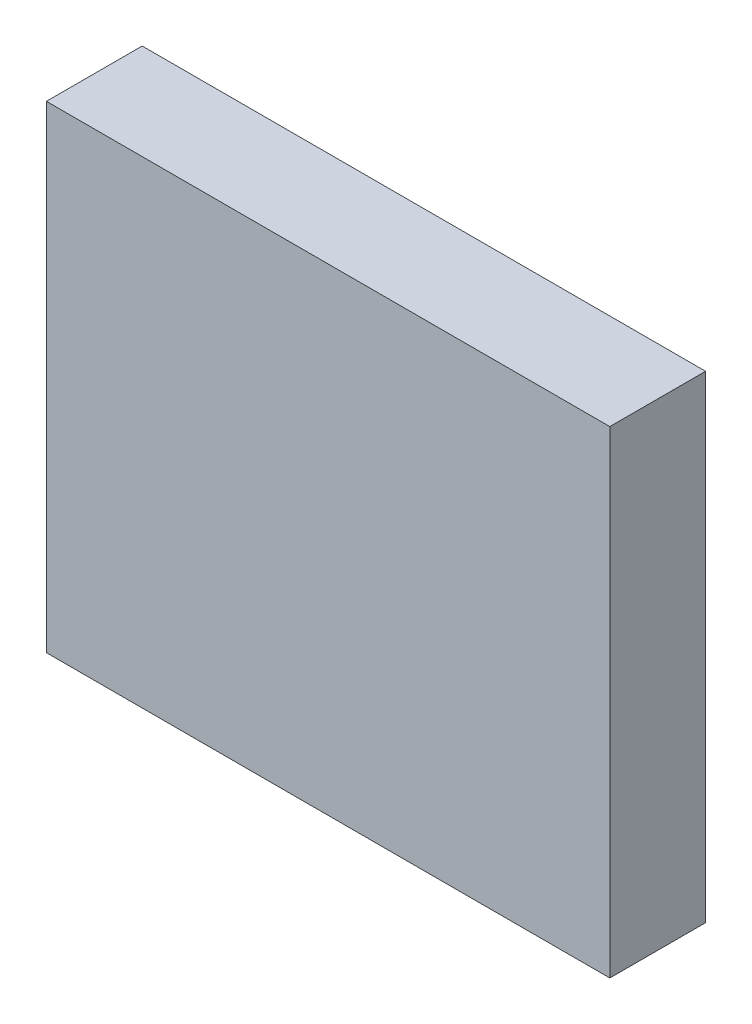
SolidWorks part; units mm, degrees
ref_plane "Front Plane" through (0, 0, 0) normal (0, 0, 1) x (1, 0, 0)
ref_plane "Top Plane" through (0, 0, 0) normal (0, 1, 0) x (1, 0, 0)
ref_plane "Right Plane" through (0, 0, 0) normal (1, 0, 0) x (0, 0, -1)
sketch "Sketch2" plane through (0, 0, 0) normal (0, 0, 1) x (1, 0, 0)
  line L1 (10.5, -8.9) -> (-10.5, -8.9)
  line L2 (10.5, -8.9) -> (10.5, 8.9)
  line L3 (10.5, 8.9) -> (-10.5, 8.9)
  line L4 (-10.5, -8.9) -> (-10.5, 8.9)
  line L5 (10.5, -8.9) -> (-10.5, 8.9) construction
  line L6 (10.5, 8.9) -> (-10.5, -8.9) construction
  point P0 (0, 0)
  point P8 (0, 0)
  dimension "D1" = 17.8
  dimension "D2" = 21
extrude "Boss-Extrude1" add sketch "Sketch2" along normal blind 3.57 contours L4 L3 L2 L1
